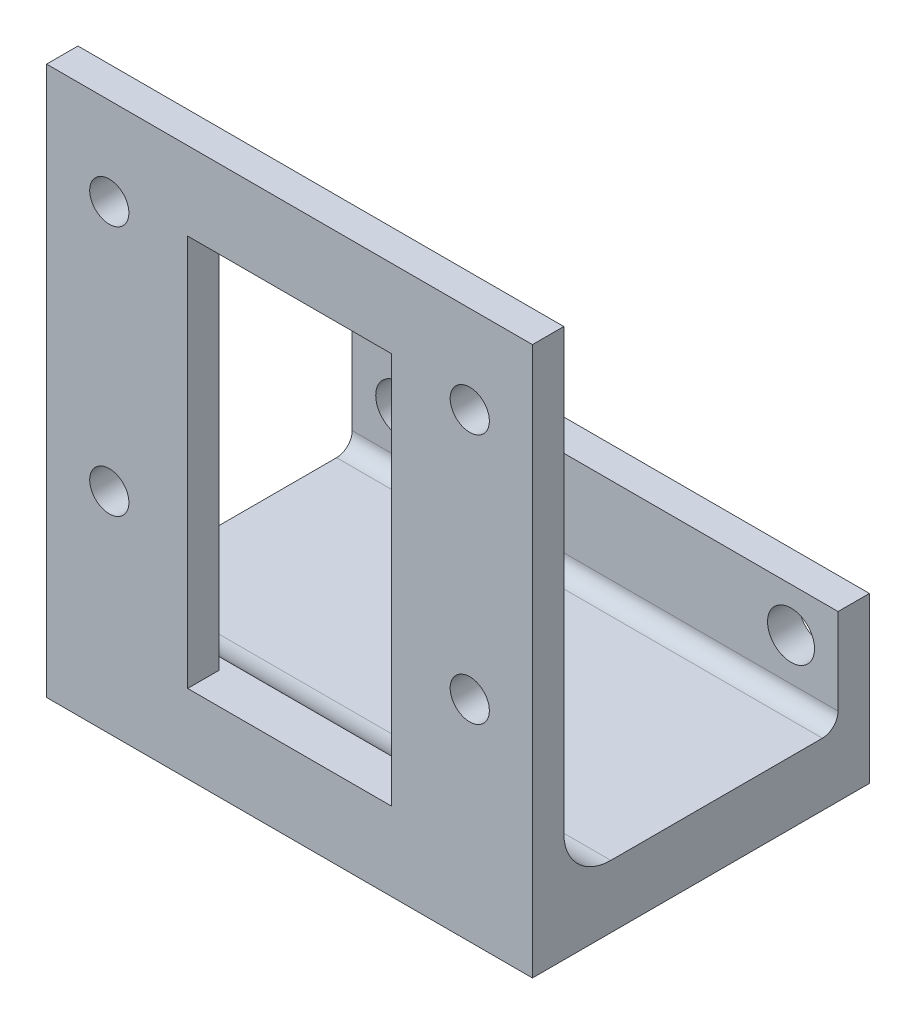
SolidWorks part; units mm, degrees
ref_plane "Front Plane" through (0, 0, 0) normal (0, 0, 1) x (1, 0, 0)
ref_plane "Top Plane" through (0, 0, 0) normal (0, 1, 0) x (1, 0, 0)
ref_plane "Right Plane" through (0, 0, 0) normal (1, 0, 0) x (0, 0, -1)
sketch "Sketch1" plane through (0, 0, 0) normal (0, 0, 1) x (1, 0, 0)
  line L1 (8, 2) -> (-8, 2)
  line L2 (8, 2) -> (8, -2)
  line L3 (8, -2) -> (-8, -2)
  line L4 (-8, 2) -> (-8, -2)
  line L5 (8, 2) -> (-8, -2) construction
  line L6 (8, -2) -> (-8, 2) construction
  point P0 (0, 0)
extrude "Boss-Extrude1" add sketch "Sketch1" along normal blind 25
sketch "Sketch2" plane through (0, 0, 25) normal (0, 0, 1) x (1, 0, 0)
  line L0 (-8, -2) -> (8, -2)
  line L1 (-8, -2) -> (-8, 33)
  line L2 (8, -2) -> (8, 33)
  line L3 (-8, 33) -> (8, 33)
extrude "Boss-Extrude2" add sketch "Sketch2" along normal blind 2
fillet "Fillet1" radius 3 1 edges at (0, 2, 25)
sketch "Sketch9" plane through (0, 2, 0) normal (0, 1, 0) x (1, 0, 0)
  line L0 (-8, 0) -> (8, 0)
  line L1 (-8, 0) -> (-8, -5.5)
  line L2 (8, 0) -> (8, -5.5)
  line L3 (-8, -5.5) -> (8, -5.5)
extrude "Cut-Extrude6" cut sketch "Sketch9" against normal blind 10
sketch "Sketch10" plane through (0, 2, 0) normal (0, 1, 0) x (1, 0, 0)
  line L0 (-8, -5.5) -> (8, -5.5)
  line L1 (-8, -5.5) -> (-8, -7.5)
  line L2 (8, -5.5) -> (8, -7.5)
  line L3 (-8, -7.5) -> (8, -7.5)
extrude "Boss-Extrude4" add sketch "Sketch10" along normal blind 8
sketch "Sketch12" plane through (0, 0, 7.5) normal (0, 0, 1) x (1, 0, 0)
  line L0 (5, 6) -> (-5, 6)
  line L4 (0, 6) -> (0, 10)
  line L5 (-8, 10) -> (8, 10) construction
  circle A1 centre (5, 5.6935) radius 1.5
  point P3 (0, 6)
extrude "Cut-Extrude7" cut sketch "Sketch12" against normal blind 10
sketch "Sketch13" plane through (0, 0, 27) normal (0, 0, 1) x (1, 0, 0)
  line L0 (8, 33) -> (8, 27.4)
  line L1 (8, -2) -> (8, 33) construction
  line L2 (8, 33) -> (8, 27.4)
  line L3 (8, 33) -> (4, 33)
  line L5 (4, 33) -> (4, 27.4)
  line L6 (4, 27.4) -> (4, 11.4)
  circle A0 centre (4, 27.4) radius 1
  circle A1 centre (4, 11.4) radius 1
extrude "Cut-Extrude8" cut sketch "Sketch13" against normal blind 10
sketch "Sketch14" plane through (-8, 0, 0) normal (-1, 0, 0) x (0, 0, 1)
  line L0 (5.5, 10) -> (7.5, 10) construction
  line L1 (27, 33) -> (25, 33) construction
  line L2 (7.5, 10) -> (7.5, 2) construction
  line L3 (5.5, -2) -> (5.5, 10) construction
  line L4 (27, -2) -> (5.5, -2) construction
  line L5 (27, 33) -> (27, -2) construction
  line L6 (25, 33) -> (25, 5) construction
  line L7 (22, 2) -> (7.5, 2) construction
  line L8 (5.5, 10) -> (7.5, 10)
  line L9 (27, 33) -> (25, 33)
  line L10 (7.5, 10) -> (7.5, 2)
  line L11 (5.5, -2) -> (5.5, 10)
  line L12 (27, -2) -> (5.5, -2)
  line L13 (27, 33) -> (27, -2)
  line L14 (25, 33) -> (25, 5)
  line L15 (22, 2) -> (7.5, 2)
  arc A0 (22, 2) -> (25, 5) centre (22, 5) ccw construction
  arc A1 (22, 2) -> (25, 5) centre (22, 5) ccw
extrude "Boss-Extrude5" add sketch "Sketch14" along normal blind 17
sketch "Sketch15" plane through (0, 0, 5.5) normal (0, 0, -1) x (-1, 0, 0)
  line L0 (-8, 10) -> (25, 10)
  line L1 (-8, 10) -> (-8, 8.5)
  line L2 (25, 10) -> (25, 8.5)
  line L3 (-8, 8.5) -> (25, 8.5)
extrude "Cut-Extrude9" cut sketch "Sketch15" against normal blind 10
sketch "Sketch17" plane through (0, 0, 27) normal (0, 0, 1) x (1, 0, 0)
  line L0 (-8.5, 33) -> (-8.5, -2)
  line L1 (8, 33) -> (-25, 33) construction
  line L2 (-25, -2) -> (8, -2) construction
  line L4 (-1, 28) -> (-16, 28)
  line L5 (-1, 28) -> (-1, 3)
  line L6 (-1, 3) -> (-16, 3)
  line L7 (-16, 28) -> (-16, 3)
  line L8 (-1, 28) -> (-16, 3) construction
  line L9 (-1, 3) -> (-16, 28) construction
  point P6 (-8.5, 15.5)
extrude "Cut-Extrude11" cut sketch "Sketch17" against normal blind 10 contours L4 L7 L6 L0 | L6 L5 L4 L0
sketch "Sketch18" plane through (0, 0, 25) normal (0, 0, -1) x (-1, 0, 0)
  line L0 (-4, 11.4) -> (19, 11.4)
  line L1 (-4, 27.4) -> (19, 27.4)
  circle A1 centre (19, 11.4) radius 1.1
  circle A2 centre (19, 27.4) radius 1.1
  circle A3 centre (-4, 27.4) radius 1.1
  circle A4 centre (-4, 11.4) radius 1.1
extrude "Cut-Extrude12" cut sketch "Sketch18" against normal blind 27
sketch "Sketch19" plane through (0, 0, 5.5) normal (0, 0, -1) x (-1, 0, 0)
  line L0 (19, 27.4) -> (23, 27.4)
  line L1 (19, 11.4) -> (23, 11.4)
  line L2 (23, 33) -> (23, -2)
  line L3 (-8, 33) -> (25, 33) construction
  line L4 (25, -2) -> (-8, -2) construction
  line L5 (23, -2) -> (25, -2)
  line L6 (25, -2) -> (25, 33)
  line L7 (25, 33) -> (23, 33)
extrude "Cut-Extrude13" cut sketch "Sketch19" against normal blind 27 contours L6 L7 L2 L5
sketch "Sketch21" plane through (0, 0, 27) normal (0, 0, 1) x (1, 0, 0)
  line L0 (-19, 27.4) -> (-14, 27.4)
  line L1 (-19, 11.4) -> (-14, 11.4)
  line L2 (-14, 27.4) -> (-14, 28)
  line L3 (-1, 28) -> (-16, 28) construction
  line L4 (-14, 28) -> (-16, 28)
  line L5 (-16, 28) -> (-16, 3)
  line L6 (-16, 3) -> (-14, 3)
  line L7 (-1, 3) -> (-16, 3) construction
  line L8 (-14, 3) -> (-14, 28)
  line M7 (-16, 3) -> (-16, 28)
  line M10 (-1, 3) -> (-16, 3)
extrude "Boss-Extrude6" add sketch "Sketch21" against normal up to surface (2 mm away) contours L1 L8 L0 M7 | L8 L1 M10 M7 up to face at (-8, 17.75, 25)
sketch "Sketch22" plane through (0, 0, 5.5) normal (0, 0, -1) x (-1, 0, 0)
  line L0 (-5, 5.6935) -> (-5, 8.5)
  line L1 (-8, 8.5) -> (23, 8.5) construction
  line L2 (-5, 8.5) -> (23, 8.5)
  line L3 (23, 8.5) -> (23, 5.6935)
  line L4 (23, 8.5) -> (23, -2) construction
  line L5 (23, 5.6935) -> (20, 5.6935)
  circle A0 centre (20, 5.6935) radius 1.5
extrude "Cut-Extrude14" cut sketch "Sketch22" against normal blind 11
fillet "Fillet2" radius 1 1 edges at (-7.5, 2, 7.5)
sketch "Sketch23" plane through (0, 0, 27) normal (0, 0, 1) x (1, 0, 0)
  circle A0 centre (4, 27.4) radius 1.25
  circle A1 centre (4, 11.4) radius 1.25
  circle A2 centre (-19, 11.4) radius 1.25
  circle A3 centre (-19, 27.4) radius 1.25
extrude "Cut-Extrude15" cut sketch "Sketch23" against normal blind 10
